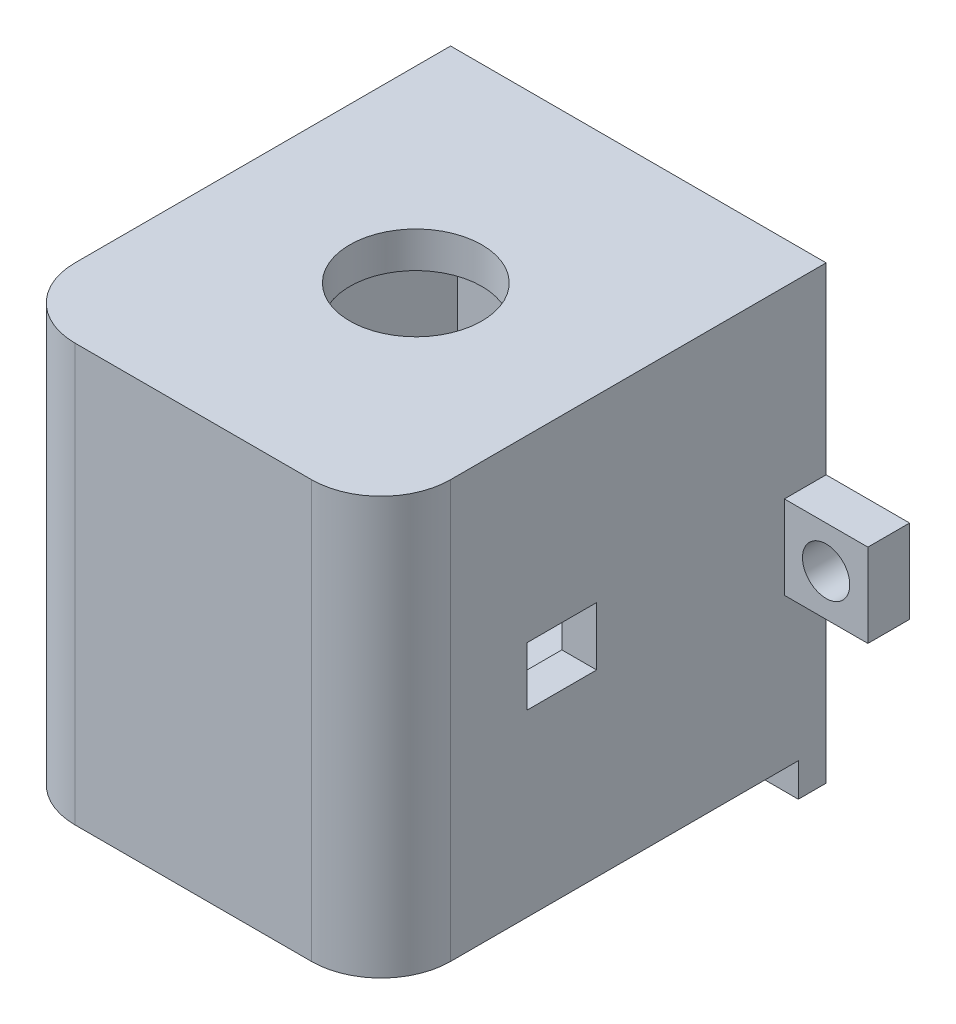
SolidWorks part; units mm, degrees
ref_plane "Front Plane" through (0, 0, 0) normal (0, 0, 1) x (1, 0, 0)
ref_plane "Top Plane" through (0, 0, 0) normal (0, 1, 0) x (1, 0, 0)
ref_plane "Right Plane" through (0, 0, 0) normal (1, 0, 0) x (0, 0, -1)
sketch "Sketch1" plane through (0, 0, 0) normal (0, 0, 1) x (1, 0, 0)
  line L1 (13.5, -13.8) -> (-13.5, -13.8)
  line L2 (13.5, -13.8) -> (13.5, 16.2)
  line L3 (13.5, 16.2) -> (-13.5, 16.2)
  line L4 (-13.5, -13.8) -> (-13.5, 16.2)
  line L7 (11, -11.3915) -> (-11, -11.3915)
  line L8 (11, -11.3915) -> (11, 13.6085)
  line L9 (11, 13.6085) -> (-11, 13.6085)
  line L10 (-11, -11.3915) -> (-11, 13.6085)
  line L11 (11, -11.3915) -> (-11, 13.6085) construction
  line L12 (11, 13.6085) -> (-11, -11.3915) construction
  point P0 (0, 0)
  point P6 (0, 1.1085)
  dimension "D1" = 27
  dimension "D2" = 22
  dimension "D3" = 25
  dimension "D4" = 30
extrude "Boss-Extrude1" add sketch "Sketch1" along normal blind 28
sketch "Sketch2" plane through (-13.5, 0, 0) normal (-1, 0, 0) x (0, 0, 1)
  line L2 (0, 1.2) -> (28, 1.2) construction
  line L3 (0, 16.2) -> (0, -13.8) construction
  line L4 (28, 16.2) -> (28, -13.8) construction
  circle A0 centre (17, 1.2) radius 2.5
  dimension "D1" = 5
  dimension "D2" = 11
extrude "Cut-Extrude1" cut sketch "Sketch2" against normal mid plane 28
sketch "Sketch3" plane through (13.5, 0, 0) normal (1, 0, 0) x (0, 0, -1)
  line L0 (-17, 1.2) -> (-28, 1.2) construction
  line L3 (-14.5, -0.9) -> (-19.5, -0.9)
  line L4 (-14.5, -0.9) -> (-14.5, 3.3)
  line L5 (-14.5, 3.3) -> (-19.5, 3.3)
  line L6 (-19.5, -0.9) -> (-19.5, 3.3)
  line L7 (-14.5, -0.9) -> (-19.5, 3.3) construction
  line L8 (-14.5, 3.3) -> (-19.5, -0.9) construction
  line L10 (-28, -13.8) -> (-28, 16.2) construction
  point P8 (-17, 1.2)
  dimension "D1" = 5
  dimension "D2" = 4.2
  dimension "D3" = 11
extrude "Cut-Extrude2" cut sketch "Sketch3" against normal mid plane 28
sketch "Sketch4" plane through (0, -13.8, 0) normal (0, -1, 0) x (1, 0, 0)
  line L0 (-13.5, 28) -> (13.5, 0) construction
  line L1 (13.5, 28) -> (13.5, 0) construction
  line L2 (-13.5, 0) -> (13.5, 0) construction
  line L3 (13.5, 28) -> (-13.5, 0) construction
  circle A0 centre (0, 14) radius 4.75
  dimension "D1" = 9.5
extrude "Cut-Extrude3" cut sketch "Sketch4" against normal blind 58
sketch "Sketch5" plane through (0, 0, 28) normal (0, 0, 1) x (1, 0, 0)
  line L1 (13.5, -13.8) -> (-13.5, -13.8)
  line L2 (13.5, -13.8) -> (13.5, 16.2)
  line L3 (13.5, 16.2) -> (-13.5, 16.2)
  line L4 (-13.5, -13.8) -> (-13.5, 16.2)
  line L6 (13.5, 16.2) -> (-13.5, -13.8) construction
  point P0 (0, 0)
extrude "Boss-Extrude2" add sketch "Sketch5" along normal blind 2
sketch "Sketch6" plane through (0, 0, 0) normal (0, 0, -1) x (-1, 0, 0)
  line L1 (13.5, -16.2) -> (-13.5, -16.2)
  line L2 (13.5, -16.2) -> (13.5, 16.2)
  line L3 (13.5, 16.2) -> (-13.5, 16.2)
  line L4 (-13.5, -16.2) -> (-13.5, 16.2)
  line L5 (13.5, -16.2) -> (-13.5, 16.2) construction
  line L6 (13.5, 16.2) -> (-13.5, -16.2) construction
  point P0 (0, 0)
extrude "Boss-Extrude3" add sketch "Sketch6" along normal blind 2
sketch "Sketch7" plane through (0, 0, -2) normal (0, 0, -1) x (-1, 0, 0)
  line L0 (0, 0) -> (-13.5, 0) construction
  line L1 (-13.5, 16.2) -> (-13.5, -16.2) construction
  line L2 (-13.5, 0) -> (13.5, 0) construction
  line L3 (13.5, -16.2) -> (13.5, 16.2) construction
  line L4 (-13.5, 0) -> (-13.5, 3)
  line L5 (-13.5, 3) -> (-19.5, 3)
  line L6 (-19.5, 3) -> (-19.5, -3)
  line L7 (-19.5, -3) -> (-13.5, -3)
  line L8 (-13.5, -3) -> (-13.5, 0)
  line L9 (-13.5, 3) -> (-19.5, -3) construction
  circle A0 centre (-16.5, 0) radius 1.7
  dimension "D4" = 3.4
  dimension "D1" = 3
  dimension "D2" = 3
  dimension "D3" = 6
extrude "Boss-Extrude4" add sketch "Sketch7" against normal blind 3
mirror "Mirror2" about plane through (0, 0, 0) normal (1, 0, 0) of "Boss-Extrude4"
fillet "Fillet11" radius 5 2 edges at (13.5, 1.2, 30) (-13.5, 1.2, 30)
mirror "Mirror1" about plane through (0, 0, 0) normal (1, 0, 0) of "Boss-Extrude4"
